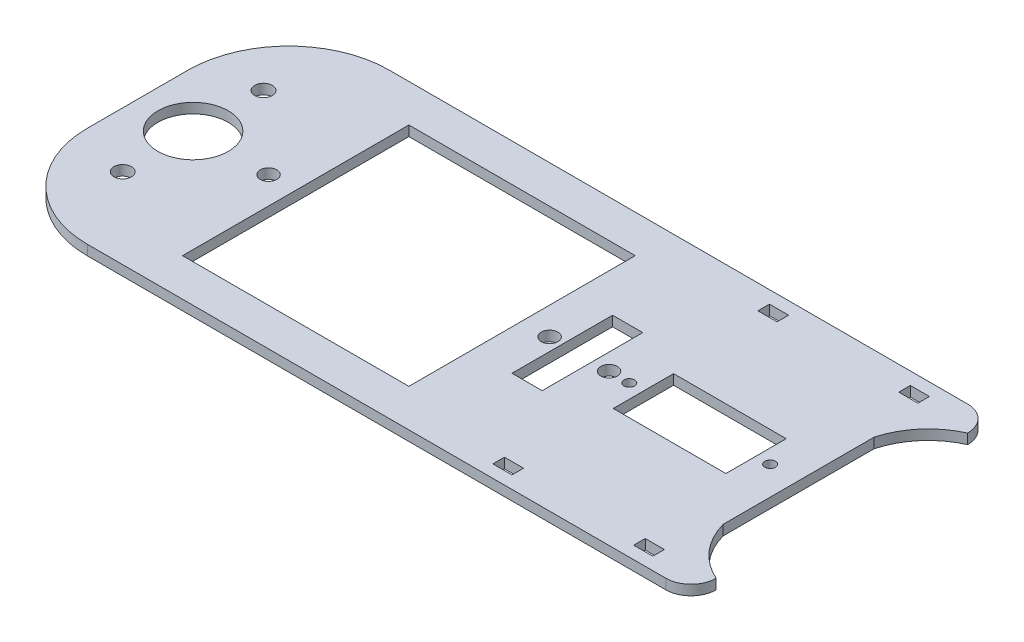
SolidWorks part; units mm, degrees
ref_plane "Front" through (0, 0, 0) normal (0, 0, 1) x (1, 0, 0)
ref_plane "Top" through (0, 0, 0) normal (0, 1, 0) x (1, 0, 0)
ref_plane "Right" through (0, 0, 0) normal (1, 0, 0) x (0, 0, -1)
sketch "Croquis1" plane through (0, 0, 0) normal (0, 1, 0) x (1, 0, 0)
  line L0 (-677.3338, 0) -> (33189.3559, 0) construction
  line L1 (0, -677.3338) -> (0, 33189.3559) construction
  line L2 (-59, -14) -> (-59, 14) construction
  line L3 (-50, -30) -> (65, -30)
  line L4 (-70, -10) -> (-70, 10)
  line L5 (-50, 30) -> (65, 30)
  line L7 (-70, -30) -> (70, 30) construction
  line L8 (-70, 30) -> (70, -30) construction
  line L9 (30.5304, -6) -> (52.9304, -6)
  line L10 (30.5304, -6) -> (30.5304, 6)
  line L11 (30, -977) -> (30, 49023) construction
  line L12 (28.1, 25.2) -> (31.9, 25.2)
  line L13 (28.1, 25.2) -> (28.1, 27.5)
  line L14 (28.1, 27.5) -> (31.9, 27.5)
  line L15 (31.9, 25.2) -> (31.9, 27.5)
  line L16 (28.1, 25.2) -> (31.9, 27.5) construction
  line L17 (28.1, 27.5) -> (31.9, 25.2) construction
  line L18 (58, -975.85) -> (58, 49024.15) construction
  line L19 (59.9, 25.2) -> (59.9, 27.5)
  line L20 (59.9, 25.2) -> (56.1, 25.2)
  line L21 (56.1, 25.2) -> (56.1, 27.5)
  line L22 (59.9, 27.5) -> (56.1, 27.5)
  line L23 (56.1, -25.2) -> (56.1, -27.5)
  line L24 (59.9, -25.2) -> (56.1, -25.2)
  line L25 (59.9, -25.2) -> (59.9, -27.5)
  line L26 (59.9, -27.5) -> (56.1, -27.5)
  line L27 (28.1, -25.2) -> (28.1, -27.5)
  line L28 (28.1, -25.2) -> (31.9, -25.2)
  line L29 (31.9, -25.2) -> (31.9, -27.5)
  line L30 (28.1, -27.5) -> (31.9, -27.5)
  line L31 (-16.06, -1000) -> (-16.06, 49000) construction
  line L32 (37, -1000) -> (37, 49000) construction
  line L33 (30.5304, 6) -> (52.9304, 6)
  line L34 (61.4029, -15) -> (61.4029, 15)
  line L35 (14.4029, -10) -> (20.4029, -10)
  line L36 (14.4029, -10) -> (14.4029, 10)
  line L37 (14.4029, 10) -> (20.4029, 10)
  line L38 (20.4029, -10) -> (20.4029, 10)
  line L39 (14.4029, -10) -> (20.4029, 10) construction
  line L40 (14.4029, 10) -> (20.4029, -10) construction
  line L41 (52.9304, -6) -> (52.9304, 6)
  line L42 (30.5304, -6) -> (52.9304, 6) construction
  line L43 (30.5304, 6) -> (52.9304, -6) construction
  line L44 (-38.596, -22.5) -> (6.404, -22.5)
  line L45 (-38.596, -22.5) -> (-38.596, 22.5)
  line L46 (-38.596, 22.5) -> (6.404, 22.5)
  line L47 (6.404, -22.5) -> (6.404, 22.5)
  line L48 (-38.596, -22.5) -> (6.404, 22.5) construction
  line L49 (-38.596, 22.5) -> (6.404, -22.5) construction
  circle A0 centre (-59, -14) radius 1.75
  circle A1 centre (-59, 14) radius 1.75
  arc A2 (65, -30) -> (70, -25) centre (65, -25) ccw
  circle A3 centre (55.7304, 0) radius 1.05
  circle A4 centre (27.7304, 0) radius 1.05
  arc A5 (70, 25) -> (65, 30) centre (65, 25) ccw
  circle A6 centre (-44, 0) radius 1.65
  circle A7 centre (11.88, 0) radius 1.65
  arc A8 (-70, 10) -> (-50, 30) centre (-50, 10) cw
  arc A9 (-50, -30) -> (-70, -10) centre (-50, -10) cw
  circle A10 centre (-59, 0) radius 7
  arc A11 (70, 25) -> (61.4029, 15) centre (76.2316, 10.9471) ccw
  arc A12 (70, -25) -> (61.4029, -15) centre (76.2316, -10.9471) cw
  circle A13 centre (23.7029, 0) radius 1.65
  point P4 (0, 0)
  point P13 (-59, 0)
  point P21 (30, 26.35)
  point P42 (41.7304, 0)
  point P45 (61.4029, 0)
  point P47 (58, 27.5)
  point P58 (-16.096, 0)
  point P66 (17.4029, 0)
  point P75 (70, 15)
  dimension "D5" = 3.5
  dimension "D6" = 50
  dimension "D12" = 30
  dimension "D14" = 26
  dimension "D15" = 3.3
  dimension "D17" = 14
  dimension "D18" = 20
  dimension "D19" = 20
  dimension "D23" = 5
  dimension "D13" = 3.3
  dimension "D16" = 55.88
  dimension "D24" = 27.94
  dimension "D27" = 14
  dimension "D33" = 2.1
  dimension "D34" = 5.6725
  dimension "D35" = 2.1
  dimension "D36" = 28
  dimension "D39" = 2.8
  dimension "D40" = 3.3
  dimension "D1" = 140
  dimension "D2" = 60
  dimension "D3" = 28
  dimension "D4" = 11
  dimension "D8" = 3.8
  dimension "D9" = 41
  dimension "D11" = 28
  dimension "D20" = 20
  dimension "D21" = 6
  dimension "D22" = 2.3
  dimension "D10" = 100
  dimension "D25" = 45
  dimension "D26" = 45
  dimension "D7" = 60
  dimension "D28" = 2.5
  dimension "D29" = 3.8
  dimension "D30" = 2.3
  dimension "D31" = 2.5
  dimension "D32" = 2.5
  dimension "D37" = 22.4
  dimension "D38" = 12
  dimension "D41" = 3.3
extrude "Saliente-Extruir1" add sketch "Croquis1" along normal blind 2
sketch "Croquis2" [suppressed] plane through (0, 2, 0) normal (0, 1, 0) x (1, 0, 0)
  line L0 (-947.5, 0) -> (49052.5, 0) construction
  line L1 (62.5, -15) -> (62.5, 15) construction
  arc A0 (44.57, -4.8734) -> (44.57, 4.8734) centre (48.07, 0) ccw
  arc A1 (41.57, 3) -> (41.57, -3) centre (41.57, 0) ccw
  arc A2 (41.57, 3) -> (44.57, 4.8734) centre (41.023, 7.2147) ccw
  arc A3 (41.57, -3) -> (44.57, -4.8734) centre (41.023, -7.2147) cw
  point P5 (62.5, 0)
  dimension "D1" = 12
  dimension "D2" = 14.43
  dimension "D3" = 6
  dimension "D4" = 6.5
  dimension "D5" = 4.25
extrude "Cortar-Extruir1" [suppressed] cut sketch "Croquis2" against normal blind 10
